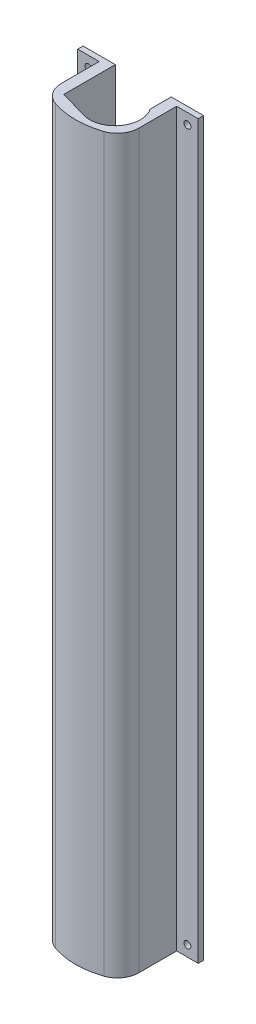
SolidWorks part; units mm, degrees
ref_plane "Front Plane" through (0, 0, 0) normal (0, 0, 1) x (1, 0, 0)
ref_plane "Top Plane" through (0, 0, 0) normal (0, 1, 0) x (1, 0, 0)
ref_plane "Right Plane" through (0, 0, 0) normal (1, 0, 0) x (0, 0, -1)
sketch "Sketch1" plane through (0, 0, 0) normal (0, 1, 0) x (1, 0, 0)
  line L0 (-20.574, -9.6521) -> (-4.162, -14.3967)
  line L1 (-4.1621, 14.3967) -> (-20.574, 9.652) construction
  line L2 (-20.574, 9.652) -> (-20.574, -9.6521)
  line L3 (-39.624, 20.7467) -> (-20.574, 20.7467)
  line L4 (-39.624, 20.7467) -> (-39.624, 17.5717)
  line L6 (12.446, 20.7467) -> (31.496, 20.7467)
  line L7 (-39.624, 17.5717) -> (-26.924, 17.5717)
  line L9 (-26.924, 17.5717) -> (-26.924, -12.8271)
  line L10 (31.496, 20.7467) -> (31.496, 17.5717)
  line L11 (31.496, 17.5717) -> (18.796, 17.5717)
  line L12 (18.796, 17.5717) -> (18.796, -12.8271)
  line L13 (-20.574, 9.652) -> (-20.574, 20.7467)
  line L14 (12.446, 20.7467) -> (12.446, 8.3478)
  arc A0 (-4.162, -14.3967) -> (12.446, 8.3478) centre (0, 0) ccw
  arc A1 (-26.924, -12.8271) -> (18.796, -12.8271) centre (-4.064, 25.294) ccw
  arc A2 (12.446, 8.3478) -> (-4.1621, 14.3967) centre (0, 0) ccw construction
  point P6 (12.446, 14.5473)
  point P16 (21.971, 20.7467)
  dimension "D2" = 14.9863
  dimension "D14" = 6.35
  dimension "D10" = 44.45
  dimension "D1" = 19.3041
  dimension "D3" = 16.4119
  dimension "D4" = 106.124
  dimension "D5" = 20.574
  dimension "D6" = 106.125
  dimension "D7" = 6.35
  dimension "D8" = 6.35
  dimension "D9" = 3.175
  dimension "D11" = 12.7
  dimension "D12" = 3.175
  dimension "D13" = 33.02
extrude "Boss-Extrude1" add sketch "Sketch1" along normal blind 431.8
sketch "Sketch2" plane through (0, 0, -17.5717) normal (0, 0, 1) x (1, 0, 0)
  line L0 (-39.624, 0) -> (-26.924, 0) construction
  line L1 (-39.624, 431.8) -> (-39.624, 0) construction
  line L2 (-39.624, 431.8) -> (-26.924, 431.8) construction
  line L3 (31.496, 431.8) -> (31.496, 0) construction
  circle A0 centre (-33.274, 425.45) radius 2.032
  circle A1 centre (-33.274, 6.35) radius 2.032
  circle A2 centre (25.146, 425.45) radius 2.032
  circle A3 centre (25.146, 6.35) radius 2.032
  dimension "D5" = 4.064
  dimension "D1" = 6.35
  dimension "D2" = 6.35
  dimension "D3" = 6.35
  dimension "D4" = 6.35
extrude "Cut-Extrude1" cut sketch "Sketch2" against normal through all
fillet "Fillet2" radius 12.7 2 edges at (18.796, 215.9, 12.8271) (-26.924, 215.9, 12.8271)
